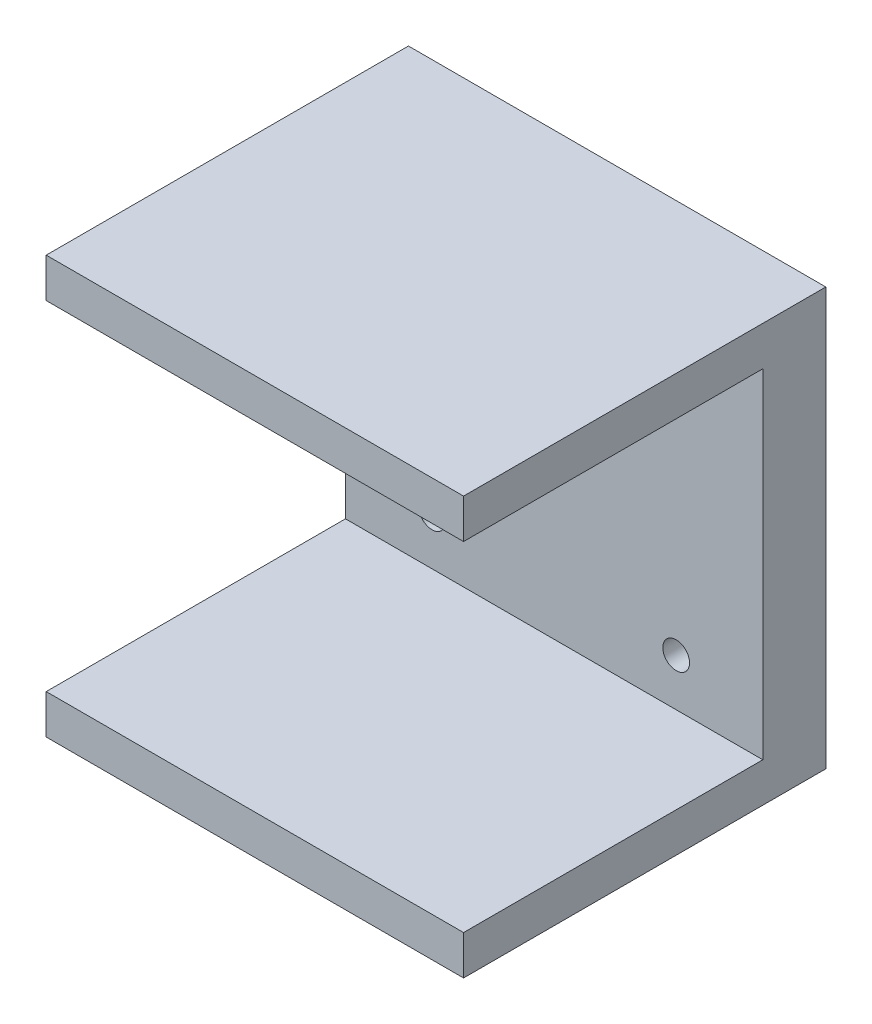
SolidWorks part; units mm, degrees
ref_plane "Front Plane" through (0, 0, 0) normal (0, 0, 1) x (1, 0, 0)
ref_plane "Top Plane" through (0, 0, 0) normal (0, 1, 0) x (1, 0, 0)
ref_plane "Right Plane" through (0, 0, 0) normal (1, 0, 0) x (0, 0, -1)
sketch "Sketch1" plane through (0, 0, 0) normal (0, 0, 1) x (1, 0, 0)
  line L1 (-26.5, -21.5) -> (26.5, -21.5)
  line L2 (-26.5, -21.5) -> (-26.5, 21.5)
  line L3 (-26.5, 21.5) -> (26.5, 21.5)
  line L4 (26.5, -21.5) -> (26.5, 21.5)
  line L5 (-26.5, -21.5) -> (26.5, 21.5) construction
  line L6 (-26.5, 21.5) -> (26.5, -21.5) construction
  point P0 (0, 0)
  dimension "D1" = 53
  dimension "D2" = 43
extrude "Boss-Extrude1" add sketch "Sketch1" along normal blind 5
sketch "Sketch2" plane through (0, 0, 0) normal (0, 0, -1) x (-1, 0, 0)
  line L16 (-26.5, -26.5) -> (26.5, -26.5)
  line L22 (-26.5, -26.5) -> (-26.5, 26.5)
  line L23 (-26.5, 26.5) -> (26.5, 26.5)
  line L24 (26.5, -26.5) -> (26.5, 26.5)
  line L25 (-26.5, -26.5) -> (26.5, 26.5) construction
  line L26 (-26.5, 26.5) -> (26.5, -26.5) construction
  line L28 (-26.5, 21.5) -> (26.5, 21.5)
  line L29 (-26.5, 21.5) -> (-26.5, -21.5)
  line L30 (-26.5, -21.5) -> (26.5, -21.5)
  line L31 (26.5, 21.5) -> (26.5, -21.5)
  point P0 (0, 0)
  dimension "D1" = 53
  dimension "D2" = 43
  dimension "D3" = 53
  dimension "D4" = 53
extrude "Boss-Extrude2" add sketch "Sketch2" against normal blind 43
sketch "Sketch4" plane through (0, 0, 0) normal (0, 0, -1) x (-1, 0, 0)
  line L1 (-15.5, 15.5) -> (15.5, 15.5) construction
  line L2 (-15.5, 15.5) -> (-15.5, -15.5) construction
  line L3 (-15.5, -15.5) -> (15.5, -15.5) construction
  line L4 (15.5, 15.5) -> (15.5, -15.5) construction
  circle A0 centre (-15.5, 15.5) radius 1.7
  circle A1 centre (15.5, 15.5) radius 1.7
  circle A2 centre (-15.5, -15.5) radius 1.7
  circle A3 centre (15.5, -15.5) radius 1.7
  point P0 (0, 0)
  dimension "D5" = 3.4
  dimension "D6" = 3.4
  dimension "D7" = 3.4
  dimension "D8" = 3.4
  dimension "D1" = 31
  dimension "D2" = 31
  dimension "D3" = 15.5
  dimension "D4" = 15.5
extrude "Cut-Extrude1" cut sketch "Sketch4" against normal through all
sketch "Sketch6" plane through (0, 0, 0) normal (0, 0, 1) x (1, 0, 0)
  line L0 (0, -26.5) -> (0, 26.5) construction
  line L1 (-26.5, 26.5) -> (26.5, 26.5)
  line L2 (-26.5, 26.5) -> (-26.5, -26.5)
  line L3 (-26.5, -26.5) -> (26.5, -26.5)
  line L4 (26.5, 26.5) -> (26.5, -26.5)
  line L5 (-26.5, 26.5) -> (26.5, -26.5) construction
  line L6 (-26.5, -26.5) -> (26.5, 26.5) construction
  line L7 (-26.5, 0) -> (26.5, 0) construction
  line L8 (-18.45, 15.5) -> (-12.55, 15.5) construction
  line L9 (-16.975, 18.0548) -> (-14.025, 12.9452) construction
  line L10 (-16.975, 12.9452) -> (-14.025, 18.0548) construction
  line L11 (-16.975, 18.0548) -> (-14.025, 18.0548) construction
  line L12 (-14.025, 18.0548) -> (-12.55, 15.5) construction
  line L13 (-12.55, 15.5) -> (-14.025, 12.9452) construction
  line L14 (-14.025, 12.9452) -> (-16.975, 12.9452) construction
  line L15 (-16.975, 12.9452) -> (-18.45, 15.5) construction
  line L16 (-18.45, 15.5) -> (-16.975, 18.0548) construction
  circle A0 centre (-15.5, 15.5) radius 2.95
  circle A1 centre (15.5, 15.5) radius 2.95
  circle A2 centre (-15.5, -15.5) radius 2.95
  circle A3 centre (15.5, -15.5) radius 2.95
  point P0 (0, 0)
  dimension "D1" = 5.9
  dimension "D2" = 60
  dimension "D3" = 60
  dimension "D4" = 53
  dimension "D5" = 53
  dimension "D6" = 15.5
  dimension "D7" = 15.5
extrude "Boss-Extrude5" add sketch "Sketch6" against normal blind 3
